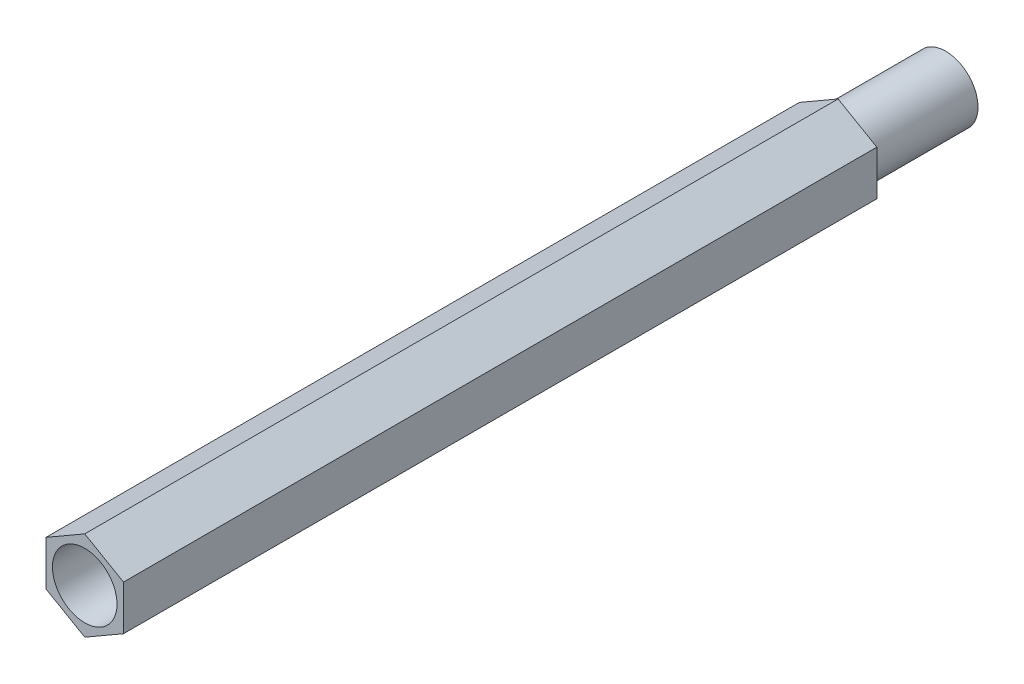
SolidWorks part; units mm, degrees
ref_plane "前视基准面" through (0, 0, 0) normal (0, 0, 1) x (1, 0, 0)
ref_plane "上视基准面" through (0, 0, 0) normal (0, 1, 0) x (1, 0, 0)
ref_plane "右视基准面" through (0, 0, 0) normal (1, 0, 0) x (0, 0, -1)
sketch "草图1" plane through (0, 0, 0) normal (0, 0, 1) x (1, 0, 0)
  line L1 (0, 2.0785) -> (-1.8, 1.0392)
  line L2 (-1.8, 1.0392) -> (-1.8, -1.0392)
  line L3 (-1.8, -1.0392) -> (0, -2.0785)
  line L4 (0, -2.0785) -> (1.8, -1.0392)
  line L5 (1.8, -1.0392) -> (1.8, 1.0392)
  line L6 (1.8, 1.0392) -> (0, 2.0785)
  circle A0 centre (0, 0) radius 1.8 construction
  circle A1 centre (0, 0) radius 1.5
extrude "凸台-拉伸1" add sketch "草图1" along normal blind 35
sketch "草图2" plane through (0, 0, 0) normal (0, 0, -1) x (-1, 0, 0)
  circle A0 centre (0, 0) radius 1.5
extrude "凸台-拉伸2" add sketch "草图2" along normal mid plane 10 contours A0
